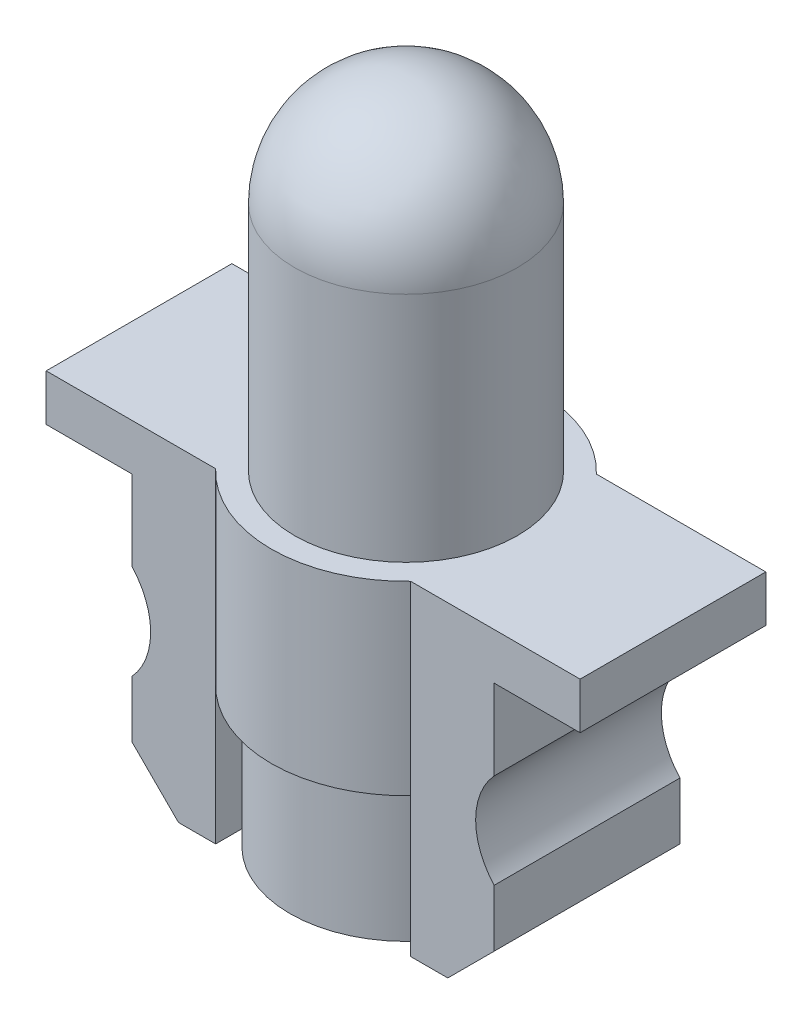
SolidWorks part; units mm, degrees
ref_plane "前视基准面" through (0, 0, 0) normal (0, 0, 1) x (1, 0, 0)
ref_plane "上视基准面" through (0, 0, 0) normal (0, 1, 0) x (1, 0, 0)
ref_plane "右视基准面" through (0, 0, 0) normal (1, 0, 0) x (0, 0, -1)
sketch "草图1" plane through (0, 0, 0) normal (0, 1, 0) x (1, 0, 0)
  line L1 (-5.75, -2) -> (5.75, -2)
  line L2 (-5.75, -2) -> (-5.75, 2)
  line L3 (-5.75, 2) -> (5.75, 2)
  line L4 (5.75, -2) -> (5.75, 2)
extrude "凸台-拉伸1" add sketch "草图1" against normal blind 1
sketch "草图2" plane through (0, 0, 0) normal (0, 1, 0) x (-1, 0, 0)
  circle A0 centre (0, 0) radius 2.9
extrude "凸台-拉伸2" add sketch "草图2" against normal blind 4
sketch "草图3" plane through (0, 0, 0) normal (0, 0, 1) x (1, 0, 0)
  line L0 (2.1, 0) -> (-2.1, 0) construction
  line L1 (0, 0) -> (2.4, 0)
  line L2 (0, 0) -> (0, 7.4)
  line L3 (0, 7.9458) -> (0, -1.6723) construction
  line L4 (2.4, 0) -> (2.4, 5)
  arc A0 (2.4, 5) -> (0, 7.4) centre (0, 5) ccw
revolve "旋转1" add sketch "草图3" angle 360 about L3
sketch "草图4" plane through (0, -4, 0) normal (0, -1, 0) x (1, 0, 0)
  circle A0 centre (0, 0) radius 2.5
extrude "凸台-拉伸3" add sketch "草图4" along normal blind 3.6
sketch "草图5" plane through (0, 0, 0) normal (0, 0, 1) x (1, 0, 0)
  line L0 (-5.75, -1) -> (-2.1, -1) construction
  line L1 (-3.9, -1) -> (-2.1, -1)
  line L2 (-3.9, -1) -> (-3.9, -7.6)
  line L3 (-3.9, -7.6) -> (-2.1, -7.6)
  line L4 (-2.1, -1) -> (-2.1, -7.6)
  line L5 (-2.5, -7.6) -> (2.5, -7.6) construction
  line L6 (-2.1, 0) -> (-2.1, -1) construction
  line L8 (2.1, -1) -> (3.9, -1)
  line L9 (2.1, -1) -> (2.1, -7.6)
  line L10 (2.1, -7.6) -> (3.9, -7.6)
  line L11 (3.9, -1) -> (3.9, -7.6)
  dimension "D1" = 6.6
extrude "凸台-拉伸4" add sketch "草图5" against normal up to surface and the other way up to surface up to face at (3.925, -0.5, -2) other way up to face at (3.925, -0.5, 2)
sketch "草图6" plane through (0, 0, 0) normal (0, 0, 1) x (1, 0, 0)
  circle A0 centre (-5, -3.75) radius 1.5
  circle A1 centre (5, -3.75) radius 1.5
extrude "切除-拉伸1" cut sketch "草图6" against normal through all and the other way through all
sketch "草图7" plane through (0, 0, 0) normal (0, 0, 1) x (1, 0, 0)
  line L0 (-3.9, -7.6) -> (3.9, -7.6)
  line L1 (-3.9, -7.6) -> (-3.9, -7)
  line L2 (3.9, -7.6) -> (3.9, -7)
  line L3 (-3.9, -7) -> (3.9, -7)
  dimension "D1" = 0.6
extrude "切除-拉伸2" cut sketch "草图7" against normal through all and the other way through all
chamfer "倒角1" distance 1 angle 45 2 edges at (3.9, -7, 0) (-3.9, -7, 0)
